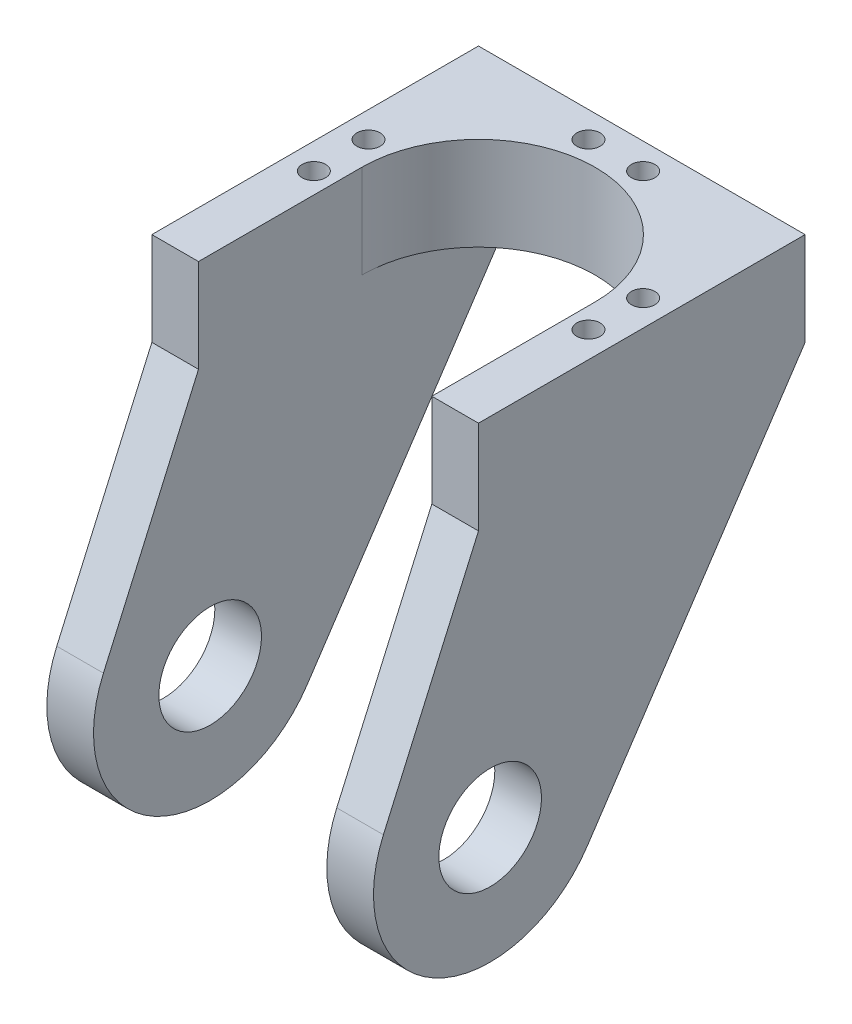
SolidWorks part; units mm, degrees
ref_plane "Front Plane" through (0, 0, 0) normal (0, 0, 1) x (1, 0, 0)
ref_plane "Top Plane" through (0, 0, 0) normal (0, 1, 0) x (1, 0, 0)
ref_plane "Right Plane" through (0, 0, 0) normal (1, 0, 0) x (0, 0, -1)
sketch "Sketch1" plane through (0, 0, 0) normal (0, 1, 0) x (1, 0, 0)
  line L0 (-5.8527, 29.4236) -> (0, 0) construction
  line L1 (0, 0) -> (11.2442, 0) construction
  line L2 (-35, 0) -> (-35, -35)
  line L3 (-35, -35) -> (35, -35)
  line L4 (35, -35) -> (35, 0)
  line L5 (-35, 0) -> (-35, 35)
  line L6 (-35, 35) -> (35, 35)
  line L7 (35, 35) -> (35, 0)
  line L8 (-25, 0) -> (-25, -35)
  line L9 (25, 0) -> (25, -35)
  circle A0 centre (0, 0) radius 35 construction
  circle A1 centre (0, 0) radius 25
  circle A2 centre (0, 0) radius 32.5 construction
  circle A4 centre (0, 0) radius 30 construction
  circle A5 centre (-5.8527, 29.4236) radius 2.5
  circle A6 centre (5.8527, 29.4236) radius 2.5
  circle A9 centre (29.4236, 5.8527) radius 2.5
  circle A10 centre (29.4236, -5.8527) radius 2.5
  circle A13 centre (5.8527, -29.4236) radius 2.5
  circle A14 centre (-5.8527, -29.4236) radius 2.5
  circle A17 centre (-29.4236, -5.8527) radius 2.5
  circle A18 centre (-29.4236, 5.8527) radius 2.5
  circle A21 centre (16.6671, 24.9441) radius 2.5 [skipped]
  circle A22 centre (24.9441, 16.6671) radius 2.5 [skipped]
  circle A23 centre (24.9441, -16.6671) radius 2.5 [skipped]
  circle A24 centre (16.6671, -24.9441) radius 2.5 [skipped]
  circle A25 centre (-16.6671, -24.9441) radius 2.5 [skipped]
  circle A26 centre (-24.9441, -16.6671) radius 2.5 [skipped]
  circle A27 centre (-24.9441, 16.6671) radius 2.5 [skipped]
  circle A28 centre (-16.6671, 24.9441) radius 2.5 [skipped]
  point P41 (0, 0)
  dimension "D1" = 70
  dimension "D2" = 50
  dimension "D3" = 65
  dimension "D4" = 60
  dimension "D5" = 5
  dimension "D6" = 101.25
  dimension "D7" = 16
extrude "Boss-Extrude1" add sketch "Sketch1" along normal blind 20 contours A1 L9 L3 L4 L7 L6 L5 L2 L8 A18 A17 A10 A9 A6 A5
sketch "Sketch7" plane through (35, 0, 0) normal (1, 0, 0) x (0, 0, -1)
  line L0 (0, 10) -> (0, -49.6631) construction
  line L1 (0, 0) -> (-32.5, -56.2917) construction
  line L2 (0, 0) -> (-35, 0) construction
  line L3 (-11.6886, -70.1439) -> (-55.3747, -46.2047) construction
  line L4 (-55.3747, -46.2047) -> (-35, 0)
  line L5 (-35, 0) -> (35, 0)
  line L6 (35, 0) -> (-11.6886, -70.1439)
  circle A0 centre (-32.5, -56.2917) radius 11
  circle A1 centre (-32.5, -56.2917) radius 25
  line M5 (-35, 0) -> (35, 0)
  dimension "D2" = 22
  dimension "D3" = 50
  dimension "D1" = 60
  dimension "D4" = 65
extrude "Boss-Extrude3" add sketch "Sketch7" against normal blind 70 contours A1 L6 L5 L4 M5 | A1 A0
sketch "Sketch9" plane through (0, 0, 0) normal (0, 0, 1) x (1, 0, 0)
  line L0 (-25, 0) -> (25, 0)
  line L1 (-25, 0) -> (-25, -83.6258)
  line L2 (25, 0) -> (25, -83.6258)
  line L3 (-25, -83.6258) -> (25, -83.6258)
  line L4 (-35, 0) -> (-25, 0) construction
  line L6 (-35, 0) -> (-25, 0) construction
  line L7 (25, 0) -> (35, 0) construction
  dimension "D1" = 10
extrude "Cut-Extrude8" cut sketch "Sketch9" along normal blind 102 and the other way blind 102 contours L0 L1 L3 L2
